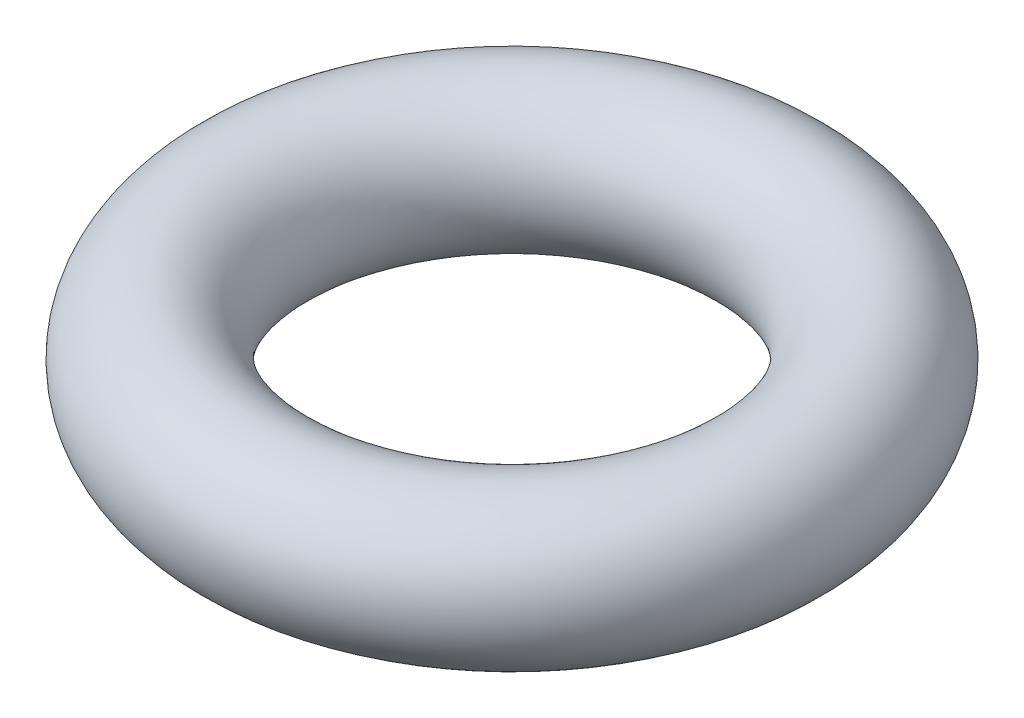
SolidWorks part; units mm, degrees
ref_plane "Front Plane" through (0, 0, 0) normal (0, 0, 1) x (1, 0, 0)
ref_plane "Top Plane" through (0, 0, 0) normal (0, 1, 0) x (1, 0, 0)
ref_plane "Right Plane" through (0, 0, 0) normal (1, 0, 0) x (0, 0, -1)
sketch "Sketch1" plane through (0, 0, 0) normal (0, 1, 0) x (1, 0, 0)
  circle A0 centre (0, 0) radius 3.5
  dimension "D1" = 7
sketch "Sketch3" plane through (0, 0, 0) normal (1, 0, 0) x (0, 0, -1)
  circle A0 centre (-3.4911, 0) radius 1
sweep "Sweep1" add profiles "Sketch3" path "Sketch1"
